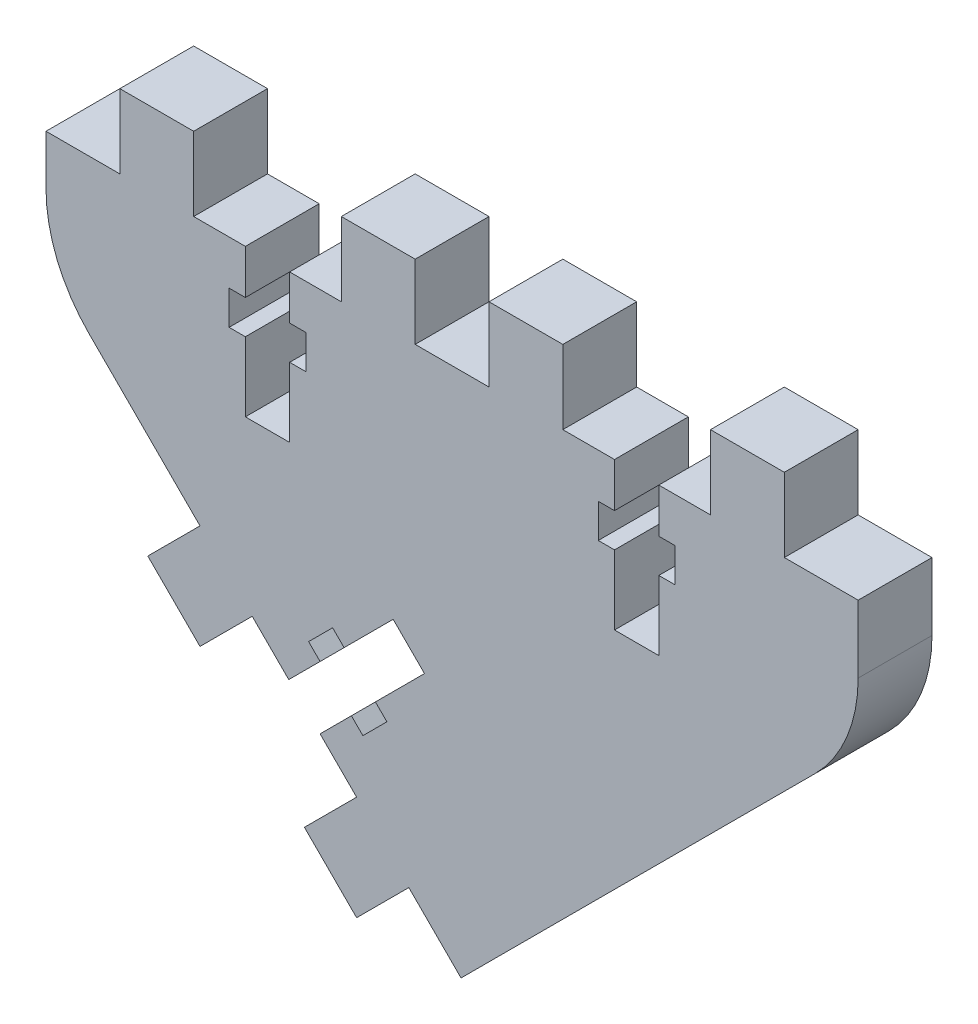
SolidWorks part; units mm, degrees
ref_plane "Plan de face" through (0, 0, 0) normal (0, 0, 1) x (1, 0, 0)
ref_plane "Plan de dessus" through (0, 0, 0) normal (0, 1, 0) x (1, 0, 0)
ref_plane "Plan de droite" through (0, 0, 0) normal (1, 0, 0) x (0, 0, -1)
sketch "Esquisse1" plane through (0, 0, 0) normal (0, 0, 1) x (1, 0, 0)
  line L0 (10, 0) -> (32.5, 0) construction
  line L1 (10, 0) -> (10, -30.9586) construction
  line L2 (-7.0711, 7.0711) -> (-10.6066, 10.6066)
  line L3 (-17.5, 17.5) -> (-17.5, 25)
  line L4 (-10.6066, 10.6066) -> (-17.5, 17.5)
  line L5 (7.5, 25) -> (12.5, 25)
  line L6 (7.0711, -7.0711) -> (10.6066, -10.6066)
  line L7 (10.6066, -10.6066) -> (37.5, 16.2868)
  line L8 (37.5, 16.2868) -> (37.5, 25)
  line L9 (37.5, 25) -> (32.5, 25)
  line L10 (-12.5, 25) -> (-17.5, 25)
  line B0 (0.2828, 3.9598) -> (1.9092, 5.5861)
  line B1 (4.8083, 2.687) -> (8.1317, 6.0104)
  line B2 (6.0104, 8.1317) -> (2.687, 4.8083)
  line B3 (1.9092, 5.5861) -> (2.687, 4.8083)
  line B4 (0, 0) -> (7.9343, 7.9343) construction
  line B5 (-1.0607, 1.0607) -> (-3.5355, 3.5355)
  line B6 (-7.0711, 0) -> (-10.6066, 3.5355)
  line B7 (-10.6066, 3.5355) -> (-7.0711, 7.0711)
  line B8 (-7.0711, 0) -> (-3.5355, 3.5355)
  line B9 (1.0607, -1.0607) -> (3.5355, -3.5355)
  line B10 (3.5355, -3.5355) -> (0, -7.0711)
  line B11 (0, -7.0711) -> (3.5355, -10.6066)
  line B12 (3.5355, -10.6066) -> (7.0711, -7.0711)
  line B13 (-1.0607, 1.0607) -> (1.0607, -1.0607) construction
  line B14 (1.0607, -1.0607) -> (3.182, 1.0607)
  line B15 (4.8083, 2.687) -> (5.5861, 1.9092)
  line B16 (3.9598, 0.2828) -> (3.182, 1.0607)
  line B17 (8.1317, 6.0104) -> (6.0104, 8.1317)
  line B18 (1.0607, 3.182) -> (0.2828, 3.9598)
  line B19 (5.5861, 1.9092) -> (3.9598, 0.2828)
  line B20 (1.0607, 3.182) -> (-1.0607, 1.0607)
  line B21 (7.0711, 7.0711) -> (0, 0) construction
  line B22 (25.1, 22) -> (25.1, 19.7)
  line B23 (21, 19.7) -> (21, 15)
  line B24 (24, 15) -> (24, 19.7)
  line B25 (25.1, 19.7) -> (24, 19.7)
  line B26 (22.5, 25) -> (22.5, 13.7792) construction
  line B27 (24, 25) -> (27.5, 25)
  line B28 (27.5, 30) -> (32.5, 30)
  line B29 (32.5, 30) -> (32.5, 25)
  line B30 (27.5, 30) -> (27.5, 25)
  line B31 (21, 25) -> (17.5, 25)
  line B32 (17.5, 25) -> (17.5, 30)
  line B33 (17.5, 30) -> (12.5, 30)
  line B34 (12.5, 30) -> (12.5, 25)
  line B35 (24, 25) -> (21, 25) construction
  line B36 (21, 25) -> (21, 22)
  line B37 (21, 19.7) -> (19.9, 19.7)
  line B38 (19.9, 22) -> (21, 22)
  line B39 (21, 15) -> (24, 15)
  line B40 (24, 22) -> (25.1, 22)
  line B41 (19.9, 19.7) -> (19.9, 22)
  line B42 (24, 22) -> (24, 25)
  line B43 (22.5, 15) -> (22.5, 25) construction
  line B44 (-5.1, 22) -> (-5.1, 19.7)
  line B45 (-1, 19.7) -> (-1, 15)
  line B46 (-4, 15) -> (-4, 19.7)
  line B47 (-5.1, 19.7) -> (-4, 19.7)
  line B48 (-2.5, 25) -> (-2.5, 13.7792) construction
  line B49 (-4, 25) -> (-7.5, 25)
  line B50 (-7.5, 30) -> (-12.5, 30)
  line B51 (-12.5, 30) -> (-12.5, 25)
  line B52 (-7.5, 30) -> (-7.5, 25)
  line B53 (-1, 25) -> (2.5, 25)
  line B54 (2.5, 25) -> (2.5, 30)
  line B55 (2.5, 30) -> (7.5, 30)
  line B56 (7.5, 30) -> (7.5, 25)
  line B57 (-4, 25) -> (-1, 25) construction
  line B58 (-1, 25) -> (-1, 22)
  line B59 (-1, 19.7) -> (0.1, 19.7)
  line B60 (0.1, 22) -> (-1, 22)
  line B61 (-1, 15) -> (-4, 15)
  line B62 (-4, 22) -> (-5.1, 22)
  line B63 (0.1, 19.7) -> (0.1, 22)
  line B64 (-4, 22) -> (-4, 25)
  line B65 (-2.5, 15) -> (-2.5, 25) construction
  dimension "D1" = 5
  dimension "D2" = 45
  dimension "D3" = 5
  dimension "D4" = 25
  dimension "D5" = 10
sketch_block_instance "Insert M3 plots ep 5mm-1"
sketch_block "Insert M3 plots ep 5mm" parameters "D1"=10, "D2"=5, "D3"=5
sketch_block_instance "Decoupe Insert M3-4"
sketch_block "Decoupe Insert M3" parameters "D1"=5.2, "D2"=3, "D3"=2.3, "D4"=3, "D5"=10
sketch_block_instance "Insert M3 plots ep 5mm-3"
sketch_block_instance "Insert M3 plots ep 5mm-4"
extrude "Boss.-Extru.1" add sketch "Esquisse1" along normal blind 5
fillet "Congé1" radius 10 2 edges at (-17.5, 17.5, 2.5) (37.5, 16.2868, 2.5)
